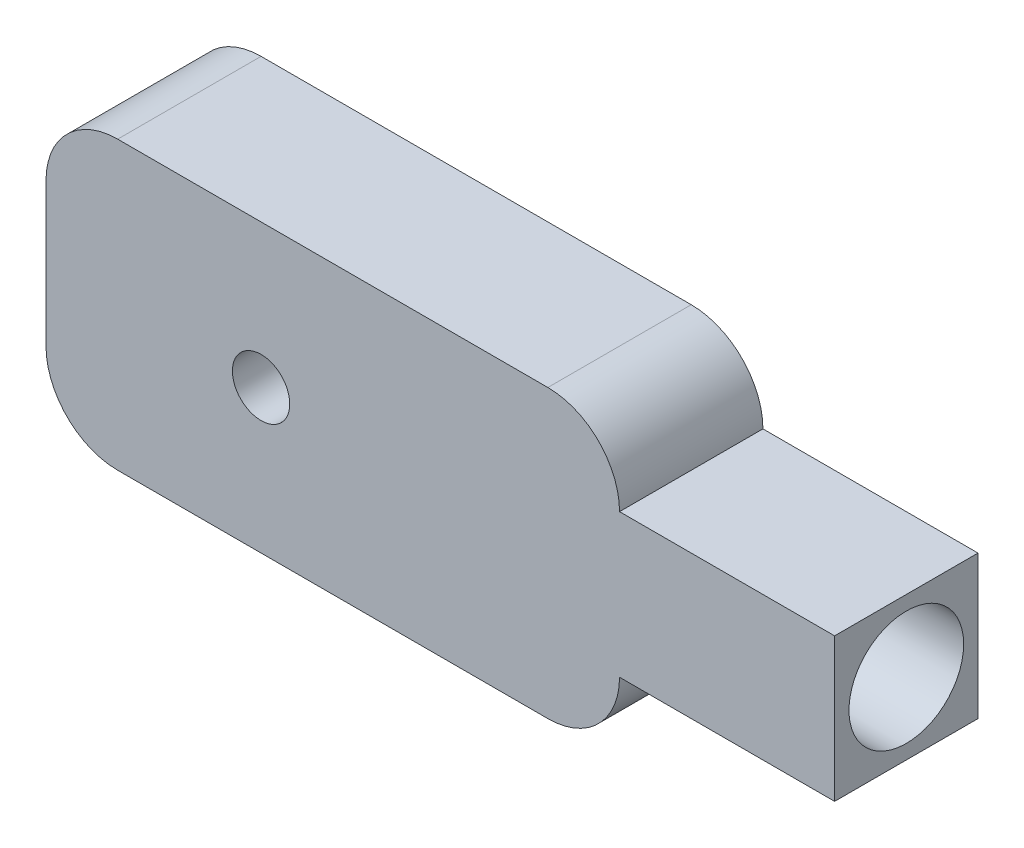
SolidWorks part; units mm, degrees
ref_plane "Front Plane" through (0, 0, 0) normal (0, 0, 1) x (1, 0, 0)
ref_plane "Top Plane" through (0, 0, 0) normal (0, 1, 0) x (1, 0, 0)
ref_plane "Right Plane" through (0, 0, 0) normal (1, 0, 0) x (0, 0, -1)
sketch "Sketch2" plane through (0, 0, 0) normal (0, 0, 1) x (1, 0, 0)
  line L1 (25.4, -12.7) -> (-25.4, -12.7)
  line L2 (25.4, -12.7) -> (25.4, 12.7)
  line L3 (25.4, 12.7) -> (-25.4, 12.7)
  line L4 (-25.4, -12.7) -> (-25.4, 12.7)
  line L5 (25.4, -12.7) -> (-25.4, 12.7) construction
  line L6 (25.4, 12.7) -> (-25.4, -12.7) construction
  point P0 (0, 0)
  dimension "D1" = 25.4
  dimension "D2" = 50.8
extrude "Boss-Extrude1" add sketch "Sketch2" along normal blind 12.7
fillet "Fillet1" radius 6.35 4 edges at (-25.4, -12.7, 6.35) (25.4, -12.7, 6.35) (-25.4, 12.7, 6.35) (25.4, 12.7, 6.35)
sketch "Sketch3" plane through (0, 0, 12.7) normal (0, 0, 1) x (1, 0, 0)
  line L0 (-25.4, 6.35) -> (-25.4, -6.35) construction
  circle A0 centre (-6.35, 0) radius 2.54
  point P3 (-25.4, 0)
  dimension "D1" = 5.08
  dimension "D2" = 19.05
extrude "Cut-Extrude1" cut sketch "Sketch3" against normal through all
sketch "Sketch4" plane through (25.4, 0, 0) normal (1, 0, 0) x (0, 0, -1)
  line L1 (0, 6.35) -> (-12.7, 6.35)
  line L2 (0, 6.35) -> (0, -6.35)
  line L3 (0, -6.35) -> (-12.7, -6.35)
  line L4 (-12.7, 6.35) -> (-12.7, -6.35)
extrude "Boss-Extrude2" add sketch "Sketch4" along normal blind 19.05
sketch "Sketch5" plane through (44.45, 0, 0) normal (1, 0, 0) x (0, 0, -1)
  line L0 (0, -6.35) -> (0, 6.35) construction
  line L1 (-12.7, -6.35) -> (0, -6.35) construction
  circle A0 centre (-6.35, 0) radius 5.08
  dimension "D3" = 10.16
  dimension "D1" = 6.35
  dimension "D2" = 6.35
extrude "Cut-Extrude2" cut sketch "Sketch5" against normal blind 25.4
